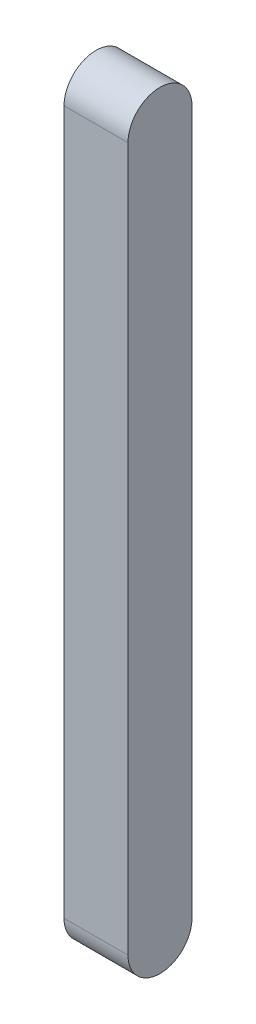
SolidWorks part; units mm, degrees
ref_plane "前视基准面" through (0, 0, 0) normal (0, 0, 1) x (1, 0, 0)
ref_plane "上视基准面" through (0, 0, 0) normal (0, 1, 0) x (1, 0, 0)
ref_plane "右视基准面" through (0, 0, 0) normal (1, 0, 0) x (0, 0, -1)
sketch "草图1" plane through (0, 0, 0) normal (1, 0, 0) x (0, 0, -1)
  line L1 (-5, 55) -> (5, 55)
  line L2 (-5, 55) -> (-5, -55)
  line L3 (-5, -55) -> (5, -55)
  line L4 (5, 55) -> (5, -55)
  line L5 (-5, 55) -> (5, -55) construction
  line L6 (-5, -55) -> (5, 55) construction
  circle A0 centre (0, 55) radius 5
  circle A1 centre (0, -55) radius 5
  point P0 (0, 0)
  point P10 (0, 0)
extrude "凸台-拉伸1" add sketch "草图1" along normal blind 10 contours A0 | L2 L3 L4 L1 | A1
